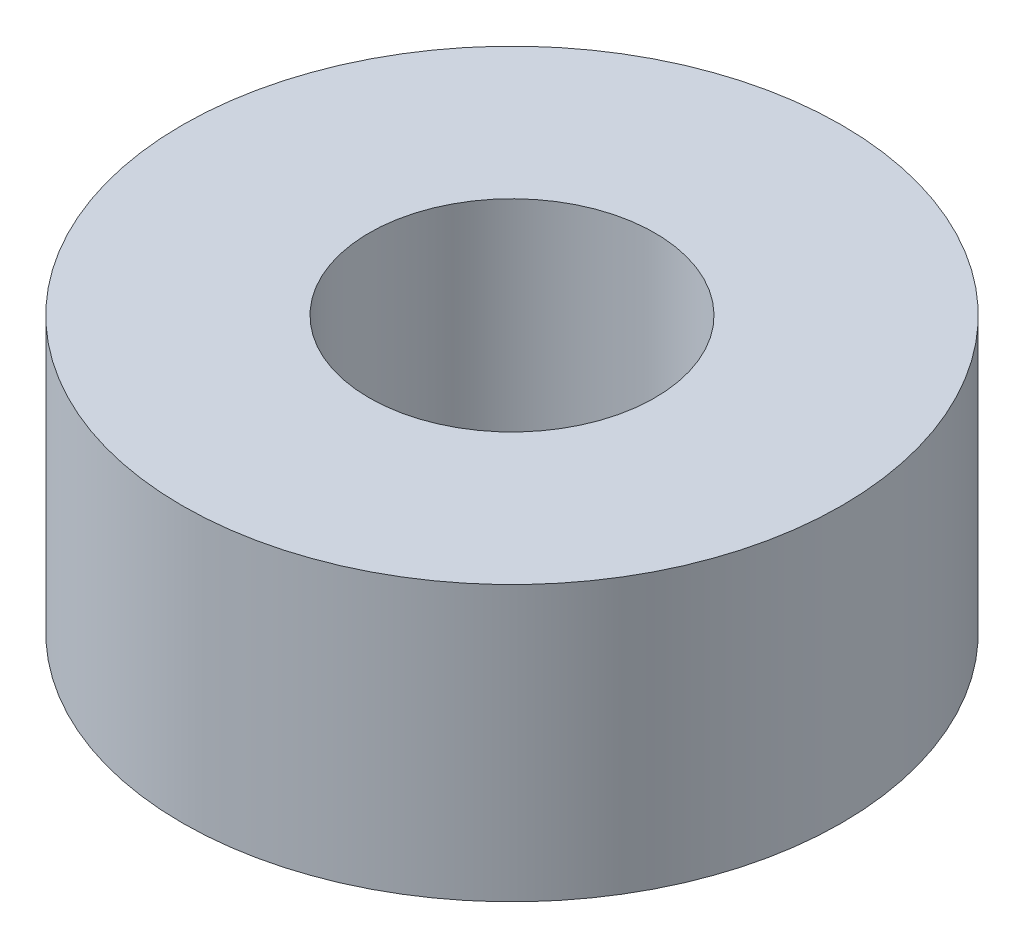
SolidWorks part; units mm, degrees
ref_plane "Front Plane" through (0, 0, 0) normal (0, 0, 1) x (1, 0, 0)
ref_plane "Top Plane" through (0, 0, 0) normal (0, 1, 0) x (1, 0, 0)
ref_plane "Right Plane" through (0, 0, 0) normal (1, 0, 0) x (0, 0, -1)
sketch "Sketch1" plane through (0, 0, 0) normal (0, 1, 0) x (1, 0, 0)
  circle A0 centre (0, 0) radius 6
  circle A1 centre (0, 0) radius 2.6
  dimension "D1" = 5.2
  dimension "D2" = 12
extrude "Boss-Extrude1" add sketch "Sketch1" along normal blind 5
